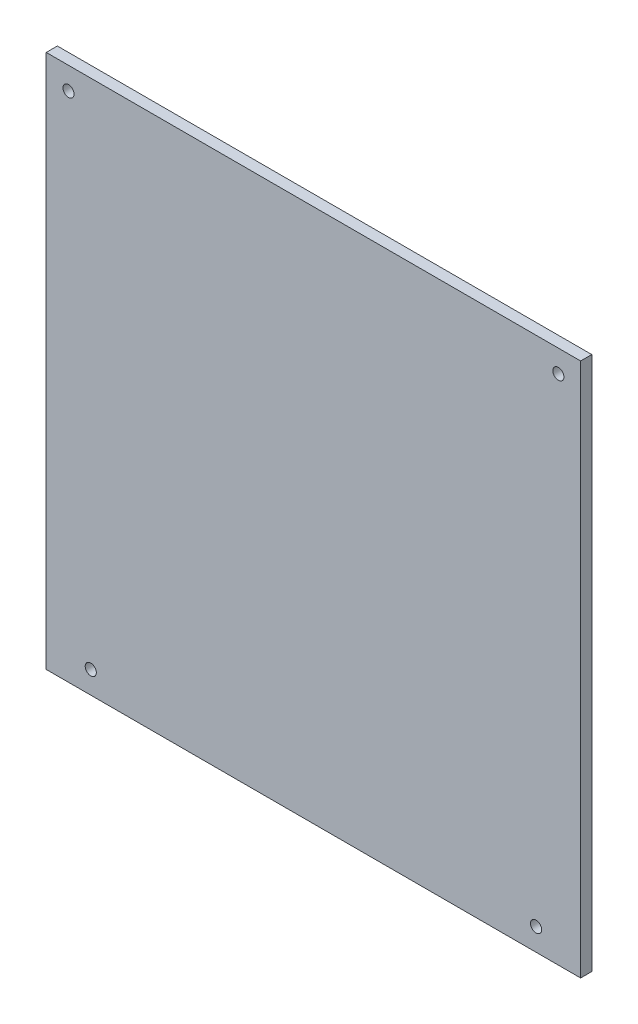
SolidWorks part; units mm, degrees
ref_plane "Front Plane" through (0, 0, 0) normal (0, 0, 1) x (1, 0, 0)
ref_plane "Top Plane" through (0, 0, 0) normal (0, 1, 0) x (1, 0, 0)
ref_plane "Right Plane" through (0, 0, 0) normal (1, 0, 0) x (0, 0, -1)
sketch "Sketch1" plane through (0, 0, 0) normal (0, 0, 1) x (1, 0, 0)
  line L5 (-139.7, 139.7) -> (139.7, 139.7) construction
  line L6 (-152.4, -152.4) -> (152.4, -152.4)
  line L7 (-152.4, -152.4) -> (-152.4, 152.4)
  line L8 (-152.4, 152.4) -> (152.4, 152.4)
  line L9 (152.4, -152.4) -> (152.4, 152.4)
  line L10 (-152.4, -152.4) -> (152.4, 152.4) construction
  line L11 (-152.4, 152.4) -> (152.4, -152.4) construction
  line L12 (-127, -139.7) -> (127, -139.7) construction
  line L13 (139.7, 139.7) -> (139.7, 152.4) construction
  line L14 (127, -139.7) -> (127, -152.4) construction
  line L15 (127, -139.7) -> (152.4, -139.7) construction
  line L16 (-127, -139.7) -> (-152.4, -139.7) construction
  circle A0 centre (139.7, 139.7) radius 3.175
  circle A1 centre (-139.7, 139.7) radius 3.175
  circle A2 centre (127, -139.7) radius 3.175
  circle A4 centre (-127, -139.7) radius 3.175
  point P0 (0, 0)
  point P2 (-110.8085, -139.7)
  dimension "D3" = 6.35
  dimension "D1" = 304.8
  dimension "D2" = 304.8
  dimension "D4" = 12.7
  dimension "D5" = 25.4
extrude "Boss-Extrude1" add sketch "Sketch1" along normal blind 6.35
equation "\"D5@Sketch1\"=\"D4@Sketch1\"*2"
